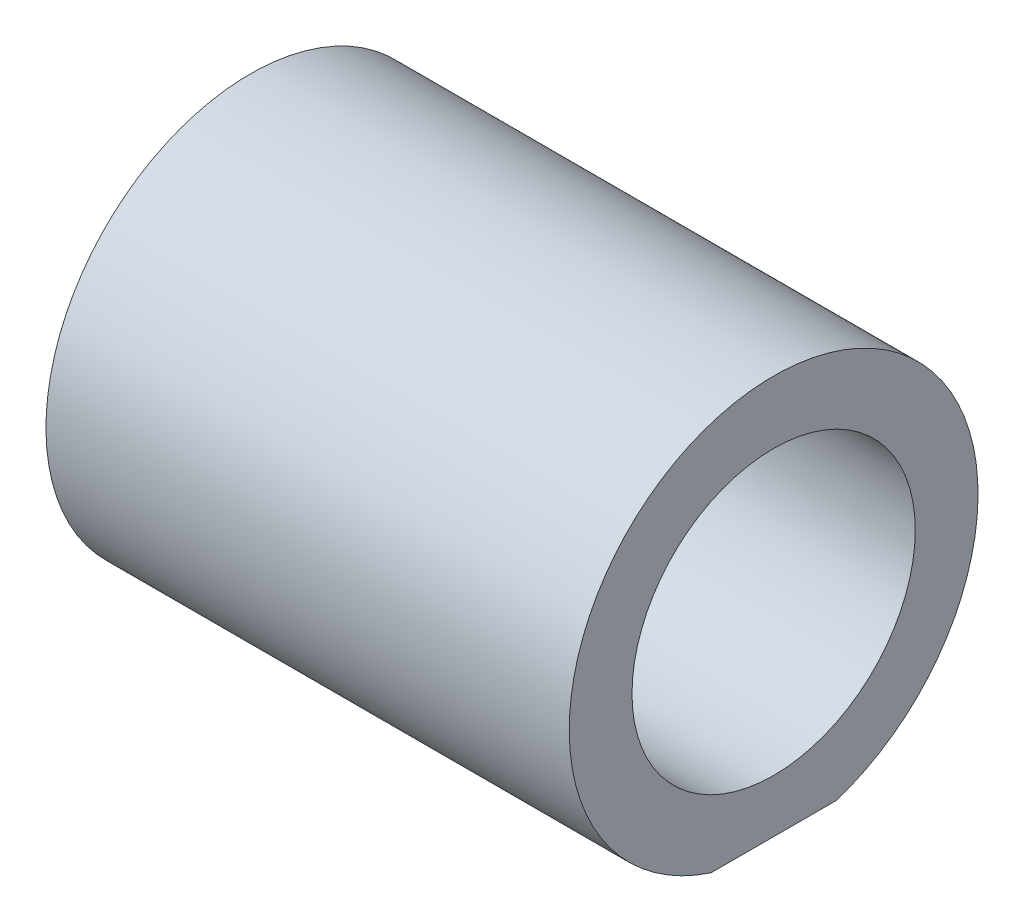
SolidWorks part; units mm, degrees
material "6061-T6 (SS)"
ref_plane "Front Plane" through (0, 0, 0) normal (1, 0, 0) x (0, 1, 0)
ref_plane "Top Plane" through (0, 0, 0) normal (0, 0, 1) x (0, 1, 0)
ref_plane "Right Plane" through (0, 0, 0) normal (0, 1, 0) x (-1, 0, 0)
sketch "Sketch1" plane through (0, 0, 0) normal (1, 0, 0) x (0, 1, 0)
  line L0 (-7.5565, -2.4297) -> (-7.5565, 2.4297)
  circle A0 centre (0, 0) radius 5.5
  arc A2 (-7.5565, 2.4297) -> (-7.5565, -2.4297) centre (0, 0) cw
  dimension "D2" = 11
  dimension "D1" = 7.9375
  dimension "D3" = 7.5565
extrude "Boss-Extrude1" add sketch "Sketch1" along normal blind 20.32
equation "\"D2@Sketch1\"=11mm"
equation "\"D3@Sketch1\"=0.5*0.625-0.015"
